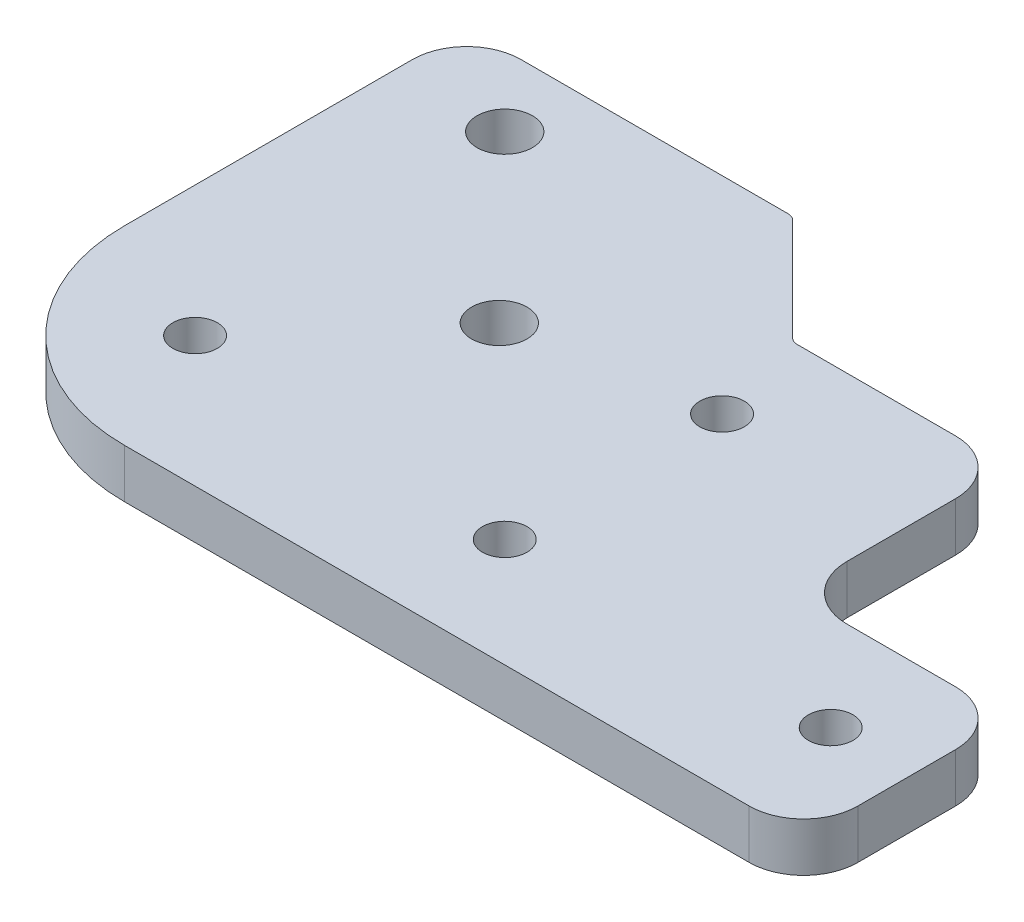
SolidWorks part; units mm, degrees
ref_plane "Front Plane" through (0, 0, 0) normal (0, 0, 1) x (1, 0, 0)
ref_plane "Top Plane" through (0, 0, 0) normal (0, 1, 0) x (1, 0, 0)
ref_plane "Right Plane" through (0, 0, 0) normal (1, 0, 0) x (0, 0, -1)
sketch "Sketch1" plane through (0, 0, 0) normal (0, 1, 0) x (1, 0, 0)
  line L0 (80, 19) -> (60, 19)
  line L1 (0, 0) -> (80, 0)
  line L2 (0, 0) -> (0, 49)
  line L3 (0, 49) -> (30, 49)
  line L4 (80, 0) -> (80, 19)
  line L5 (60, 19) -> (60, 39)
  line L6 (60, 39) -> (40, 39)
  line L7 (40, 39) -> (30, 49)
  line L8 (72.5, 10) -> (42.5, 10) construction
  line L9 (42.5, 30) -> (42.5, 10) construction
  circle A0 centre (72.5, 10) radius 2.05
  circle A1 centre (42.5, 10) radius 2.05
  circle A2 centre (42.5, 30) radius 2.05
  dimension "D9" = 4.1
  dimension "D10" = 4.1
  dimension "D13" = 4.1
  dimension "D1" = 80
  dimension "D2" = 49
  dimension "D3" = 19
  dimension "D4" = 39
  dimension "D5" = 20
  dimension "D6" = 20
  dimension "D7" = 10
  dimension "D8" = 10
  dimension "D11" = 30
  dimension "D12" = 7.5
  dimension "D14" = 20
extrude "Boss-Extrude1" add sketch "Sketch1" along normal blind 4.5
sketch "Sketch2" plane through (0, 4.5, 0) normal (0, 1, 0) x (1, 0, 0)
  line L0 (0, 0) -> (80, 0) construction
  line L1 (0, 49) -> (0, 0) construction
  circle A0 centre (25, 27) radius 2.55
  circle A1 centre (10, 42.5) radius 2.55
  circle A2 centre (12, 12) radius 2.05
  dimension "D1" = 27
  dimension "D2" = 25
  dimension "D3" = 5.1
  dimension "D5" = 42.5
  dimension "D6" = 5.1
  dimension "D7" = 12
  dimension "D8" = 12
  dimension "D9" = 4.1
  dimension "D4" = 10
extrude "Cut-Extrude1" cut sketch "Sketch2" against normal through all
fillet "Fillet1" radius 5 5 edges at (80, 2.25, 0) (80, 2.25, -19) (60, 2.25, -19) (60, 2.25, -39) (0, 2.25, -49)
fillet "Fillet2" radius 17.5 1 edges at (0, 2.25, 0)
fillet "Fillet3" radius 1 2 edges at (30, 2.25, -49) (40, 2.25, -39)
